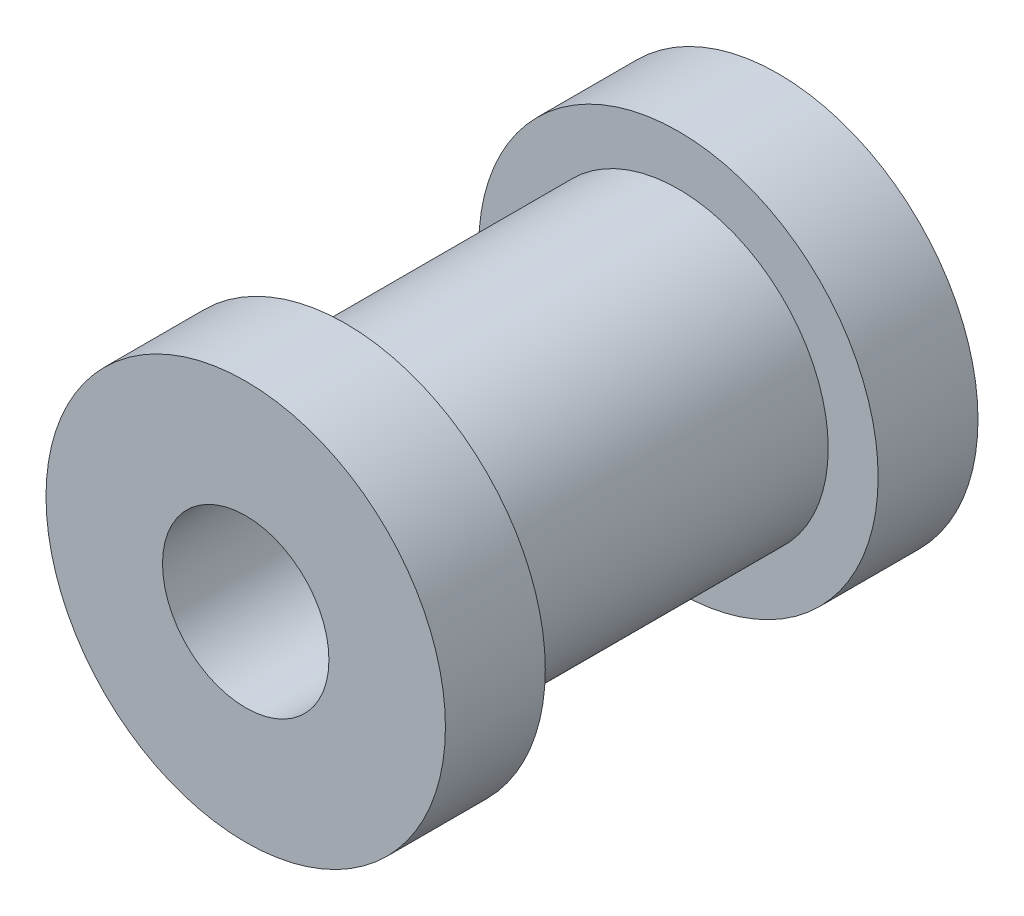
SolidWorks part; units mm, degrees
ref_plane "Спереди" through (0, 0, 0) normal (0, 0, 1) x (1, 0, 0)
ref_plane "Сверху" through (0, 0, 0) normal (0, 1, 0) x (1, 0, 0)
ref_plane "Справа" through (0, 0, 0) normal (1, 0, 0) x (0, 0, -1)
sketch "Эскиз1" plane through (0, 0, 0) normal (0, 0, 1) x (1, 0, 0)
  circle A0 centre (0, 0) radius 2.5
  circle A1 centre (0, 0) radius 6
extrude "Вытянуть1" add sketch "Эскиз1" along normal blind 16
ref_plane "Плоскость1" through (0, 0, 13) normal (0, 0, 1) x (1, 0, 0)
sketch "Эскиз2" plane through (0, 0, 13) normal (0, 0, 1) x (1, 0, 0)
  circle A0 centre (0, 0) radius 6
  circle A1 centre (0, 0) radius 4.5
extrude "Вытянуть2" cut sketch "Эскиз2" against normal blind 10
